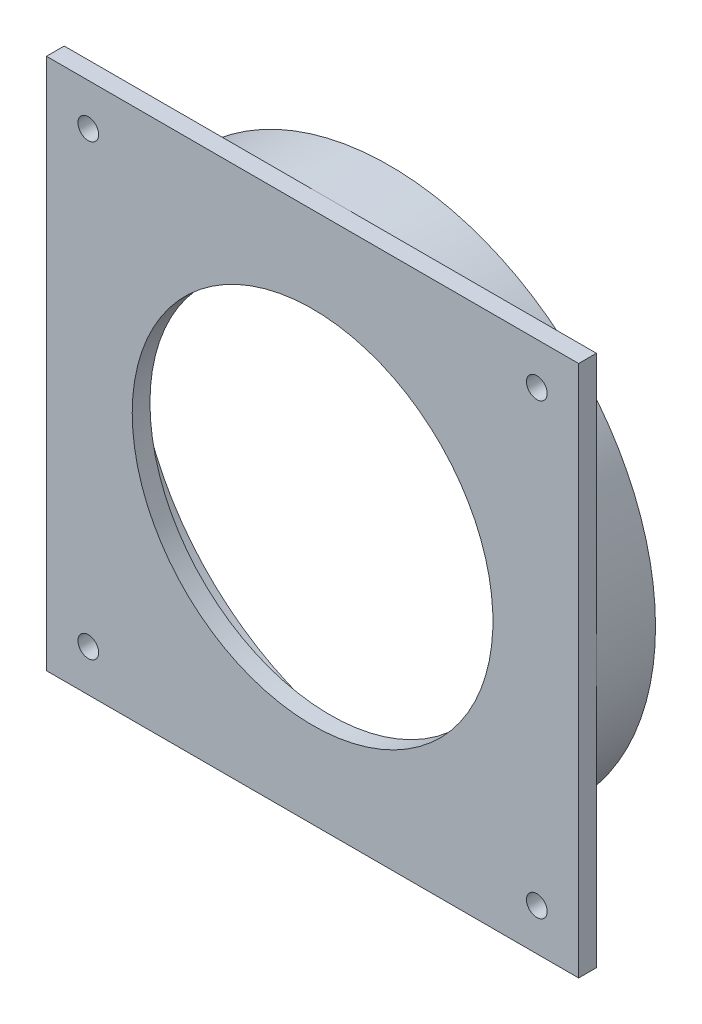
SolidWorks part; units mm, degrees
ref_plane "Front Plane" through (0, 0, 0) normal (0, 0, 1) x (1, 0, 0)
ref_plane "Top Plane" through (0, 0, 0) normal (0, 1, 0) x (1, 0, 0)
ref_plane "Right Plane" through (0, 0, 0) normal (1, 0, 0) x (0, 0, -1)
sketch "Sketch1" plane through (0, 0, 0) normal (0, 0, 1) x (1, 0, 0)
  line L1 (45, -45) -> (-45, -45)
  line L2 (45, -45) -> (45, 45)
  line L3 (45, 45) -> (-45, 45)
  line L4 (-45, -45) -> (-45, 45)
  line L5 (45, -45) -> (-45, 45) construction
  line L6 (45, 45) -> (-45, -45) construction
  point P0 (0, 0)
  dimension "D1" = 90
  dimension "D2" = 90
extrude "Boss-Extrude1" add sketch "Sketch1" along normal blind 3
sketch "Sketch9" plane through (0, 0, 0) normal (0, 0, -1) x (-1, 0, 0)
  circle A0 centre (0, 0) radius 45
  circle A1 centre (0, 0) radius 43
  dimension "D1" = 86
extrude "Boss-Extrude4" add sketch "Sketch9" along normal blind 10
sketch "Sketch11" plane through (0, 0, 0) normal (0, 0, -1) x (-1, 0, 0)
  circle A0 centre (0, 0) radius 30.5
  dimension "D1" = 61
extrude "Cut-Extrude9" cut sketch "Sketch11" against normal blind 58
sketch "Sketch14" plane through (0, 0, 3) normal (0, 0, 1) x (1, 0, 0)
  line L0 (0, 0) -> (-45, 45) construction
  line L1 (-45, 45) -> (45, -45) construction
  line L2 (45, -45) -> (45, 45) construction
  line L3 (45, 45) -> (-45, -45) construction
  circle A0 centre (-37.9289, 37.9289) radius 1.75
  circle A1 centre (37.9289, 37.9289) radius 1.75
  circle A2 centre (37.9289, -37.9289) radius 1.75
  circle A3 centre (-37.9289, -37.9289) radius 1.75
  dimension "D1" = 3.5
  dimension "D2" = 3.5
  dimension "D3" = 3.5
  dimension "D4" = 3.5
  dimension "D5" = 10
  dimension "D6" = 10
  dimension "D7" = 10
  dimension "D8" = 10
extrude "Cut-Extrude10" cut sketch "Sketch14" against normal blind 58
